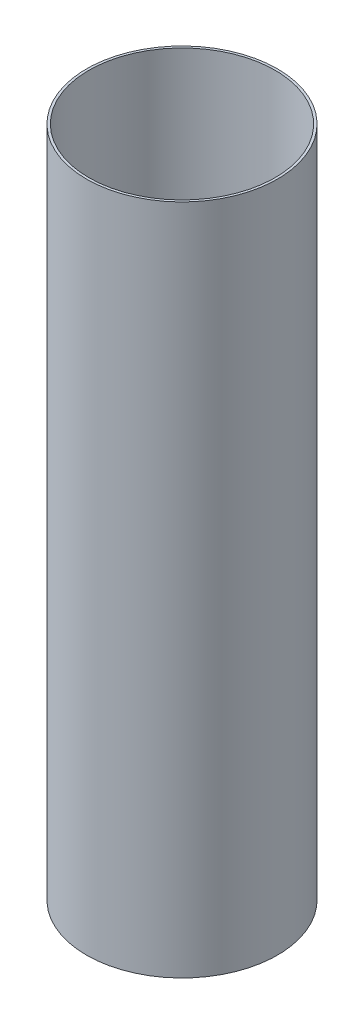
SolidWorks part; units mm, degrees
material "A-Glass Fiber"
ref_plane "Front Plane" through (0, 0, 0) normal (0, 0, 1) x (1, 0, 0)
ref_plane "Top Plane" through (0, 0, 0) normal (0, 1, 0) x (1, 0, 0)
ref_plane "Right Plane" through (0, 0, 0) normal (1, 0, 0) x (0, 0, -1)
sketch "Sketch1" plane through (0, 0, 0) normal (0, 0, 1) x (1, 0, 0)
  line L0 (78.16, 0) -> (78.16, 550)
  line L1 (76.2, 0) -> (76.2, 550)
  line L2 (78.16, 550) -> (76.2, 550)
  line L3 (76.2, 0) -> (78.16, 0)
  line L4 (0, 204.6154) -> (0, 85.8935) construction
  dimension "D1" = 76.2
  dimension "D2" = 550
  dimension "D3" = 1.96
revolve "Revolve1" add sketch "Sketch1" angle 360 about L4
